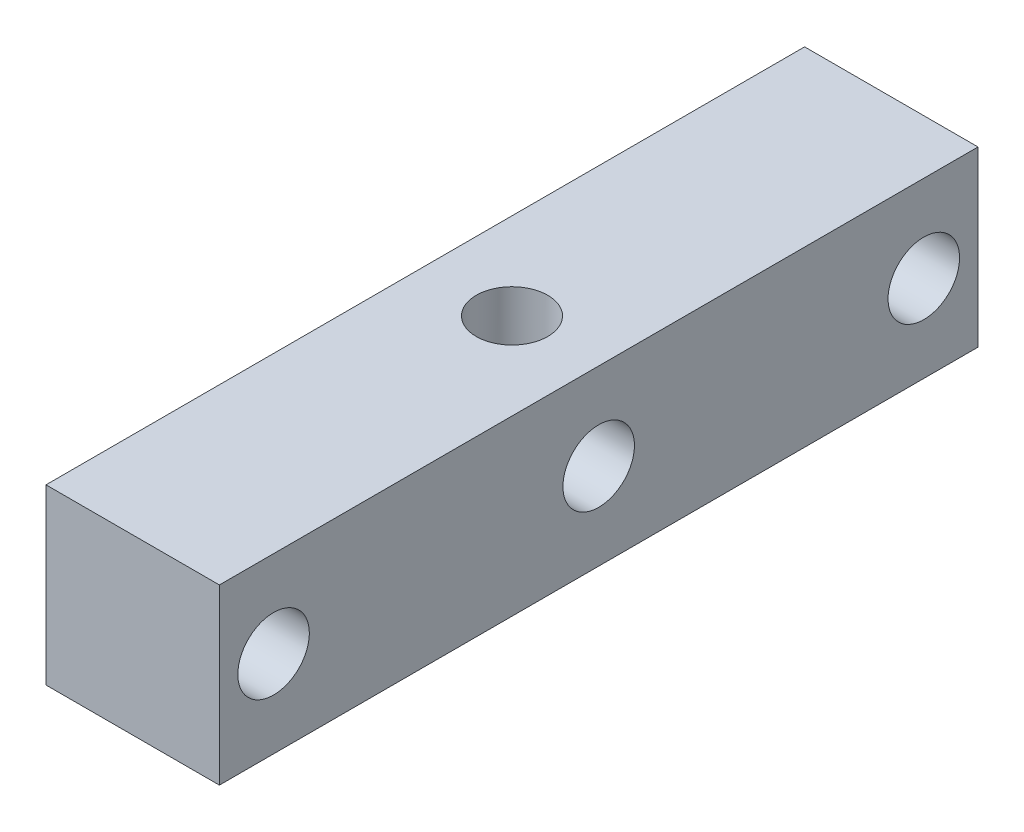
SolidWorks part; units mm, degrees
material "6061-T6 (SS)"
ref_plane "前视基准面" through (0, 0, 0) normal (0, 0, 1) x (1, 0, 0)
ref_plane "上视基准面" through (0, 0, 0) normal (0, 1, 0) x (1, 0, 0)
ref_plane "右视基准面" through (0, 0, 0) normal (1, 0, 0) x (0, 0, -1)
sketch "草图1" plane through (0, 0, 0) normal (0, 0, 1) x (1, 0, 0)
  line L1 (0, 0) -> (8, 0)
  line L2 (0, 0) -> (0, 8)
  line L3 (0, 8) -> (8, 8)
  line L4 (8, 0) -> (8, 8)
  dimension "D1" = 8
extrude "凸台-拉伸1" add sketch "草图1" along normal blind 35
sketch "草图2" plane through (8, 0, 0) normal (1, 0, 0) x (0, 0, -1)
  line L0 (-35, 4) -> (-32.5, 4) construction
  line L1 (-35, 0) -> (-35, 8) construction
  line L2 (-32.5, 4) -> (-2.5, 4) construction
  line L3 (-2.5, 4) -> (0, 4) construction
  line L4 (0, 0) -> (0, 8) construction
  circle A0 centre (-32.5, 4) radius 1.65
  circle A1 centre (-2.5, 4) radius 1.65
  dimension "D2" = 3.3
  dimension "D1" = 30
extrude "切除-拉伸1" cut sketch "草图2" against normal blind 40
cosmetic thread "装饰螺纹线1" parameters "D2"=3.675
cosmetic thread "装饰螺纹线2" parameters "D2"=3.675
sketch "草图3" plane through (0, 8, 0) normal (0, 1, 0) x (1, 0, 0)
  line L0 (4, -35) -> (4, 0) construction
  line L1 (8, -35) -> (0, -35) construction
  line L2 (8, 0) -> (0, 0) construction
  circle A0 centre (4, -17.5) radius 1.65
  dimension "D1" = 3.3
extrude "切除-拉伸2" cut sketch "草图3" against normal blind 40
cosmetic thread "装饰螺纹线3" parameters "D2"=3.675
sketch "草图5" plane through (8, 0, 0) normal (1, 0, 0) x (0, 0, -1)
  line L0 (-35, 8) -> (0, 8) construction
  line L1 (-30, 8) -> (-20, 8)
  line L2 (-30, 8) -> (-30, 4.5)
  line L3 (-29, 3.5) -> (-21, 3.5)
  line L4 (-20, 8) -> (-20, 4.5)
  line L5 (-20, 3.5) -> (-15, 3.5) construction
  line L6 (-15, 8) -> (-5, 8)
  line L7 (-15, 8) -> (-15, 4.5)
  line L8 (-14, 3.5) -> (-6, 3.5)
  line L9 (-5, 8) -> (-5, 4.5)
  line L10 (-17.5, 3.5) -> (-17.5, 0) construction
  line L11 (-35, 0) -> (0, 0) construction
  circle A0 centre (-32.5, 4) radius 1.65 construction
  arc A1 (-15, 4.5) -> (-14, 3.5) centre (-14, 4.5) ccw
  arc A2 (-6, 3.5) -> (-5, 4.5) centre (-6, 4.5) ccw
  arc A3 (-30, 4.5) -> (-29, 3.5) centre (-29, 4.5) ccw
  arc A4 (-21, 3.5) -> (-20, 4.5) centre (-21, 4.5) ccw
  dimension "D4" = 1
  dimension "D1" = 3.5
  dimension "D2" = 5
  dimension "D3" = 2.5
extrude "切除-拉伸3" [suppressed] cut sketch "草图5" against normal through all
sketch "草图6" plane through (8, 0, 0) normal (1, 0, 0) x (0, 0, -1)
  line L0 (-2.5, 4) -> (-32.5, 4) construction
  circle A0 centre (-17.5, 4) radius 1.5
  point P6 (0, 0)
  dimension "D1" = 3
extrude "切除-拉伸4" cut sketch "草图6" against normal through all
hole_wizard "M4 螺纹孔3" positions "草图9" profile "草图10" tap size "M4" standard "ISO" end condition through all
sketch "草图9" plane through (8, 0, 0) normal (1, 0, 0) x (0, 0, -1)
  point P0 (-17.5, 4)
sketch "草图10" plane through (8, 4, 17.5) normal (0, 1, 0) x (0, 0, -1)
  line L0 (0, 0) -> (0, 8)
  line L1 (0, 8) -> (1.65, 8)
  line L2 (1.65, 8) -> (1.65, 0)
  line L5 (1.65, 0) -> (0, 0)
  line L11 (0, -6.35) -> (0, 107.95) construction
  dimension "通孔螺纹孔钻头直径" = 3.3
  dimension "通孔螺纹孔钻头深度" = 8
cosmetic thread "孔螺蚊线1" parameters "D2"=4
